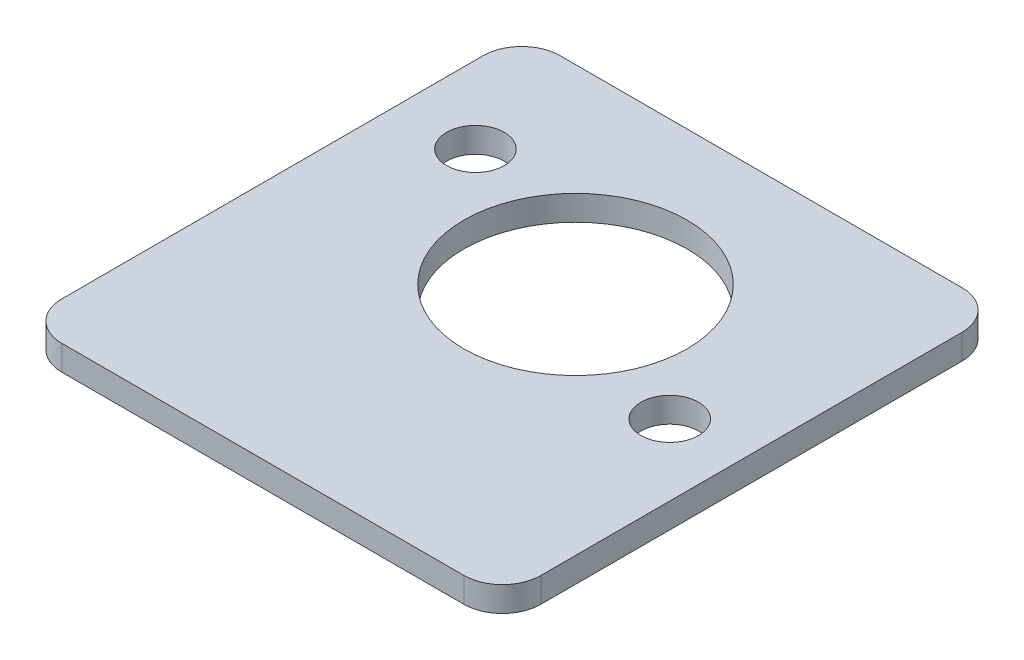
SolidWorks part; units mm, degrees
ref_plane "Front Plane" through (0, 0, 0) normal (0, 0, 1) x (1, 0, 0)
ref_plane "Top Plane" through (0, 0, 0) normal (0, 1, 0) x (1, 0, 0)
ref_plane "Right Plane" through (0, 0, 0) normal (1, 0, 0) x (0, 0, -1)
sketch "Sketch1" plane through (0, 0, 0) normal (0, 1, 0) x (1, 0, 0)
  line L1 (0, 0) -> (-63.246, 0)
  line L2 (0, 0) -> (0, 65.786)
  line L3 (0, 65.786) -> (-63.246, 65.786)
  line L4 (-63.246, 0) -> (-63.246, 65.786)
extrude "Boss-Extrude1" add sketch "Sketch1" along normal blind 3.302
fillet "Fillet2" radius 5.08 4 edges at (-63.246, 1.651, -65.786) (0, 1.651, -65.786) (0, 1.651, 0) (-63.246, 1.651, 0)
sketch "Sketch2" plane through (0, 3.302, 0) normal (0, 1, 0) x (1, 0, 0)
  circle A0 centre (-30.988, 40.64) radius 14.732
  circle A1 centre (-53.086, 49.53) radius 3.81
  circle A2 centre (-9.398, 31.496) radius 3.81
  point P0 (-30.988, 40.64)
  point P3 (-53.086, 49.53)
  point P6 (-9.398, 31.496)
extrude "Cut-Extrude1" cut sketch "Sketch2" against normal blind 9.652
